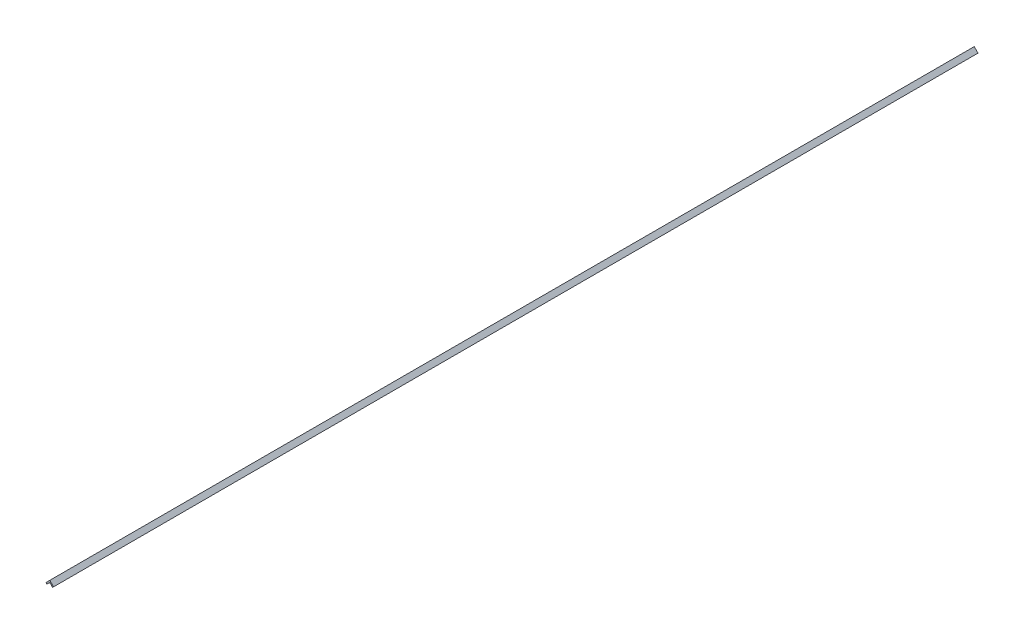
SolidWorks part; units mm, degrees
ref_plane "Plano frontal" through (0, 0, 0) normal (0, 0, 1) x (1, 0, 0)
ref_plane "Plano superior" through (0, 0, 0) normal (0, 1, 0) x (1, 0, 0)
ref_plane "Plano direito" through (0, 0, 0) normal (1, 0, 0) x (0, 0, -1)
sketch "Esboço1" plane through (0, 0, 0) normal (0, 0, 1) x (1, 0, 0)
  line L0 (0, 11.2289) -> (8.9803, 2.2486)
  line L1 (-8.9803, 2.2486) -> (-6.7317, 0)
  line L2 (0, 0) -> (0, 11.2289) construction
  line L3 (-6.7317, 0) -> (0, 6.7317)
  line L4 (8.9803, 2.2486) -> (6.7317, 0)
  line L5 (0, 11.2289) -> (-8.9803, 2.2486)
  line L6 (6.7317, 0) -> (0, 6.7317)
  dimension "D1" = 12.7
  dimension "D2" = 90
  dimension "D3" = 3.18
  dimension "D4" = 6.7317
extrude "Ressalto-extrusão1" add sketch "Esboço1" along normal blind 2200
